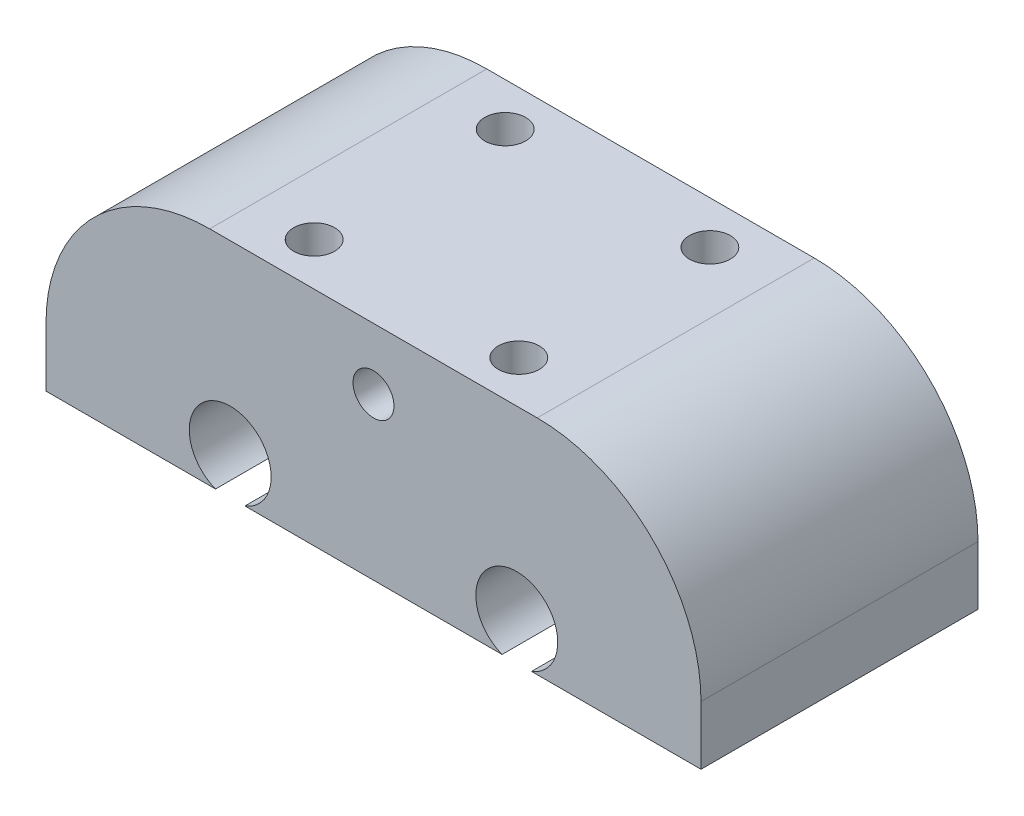
SolidWorks part; units mm, degrees
ref_plane "Front Plane" through (0, 0, 0) normal (0, 0, 1) x (1, 0, 0)
ref_plane "Top Plane" through (0, 0, 0) normal (0, 1, 0) x (1, 0, 0)
ref_plane "Right Plane" through (0, 0, 0) normal (1, 0, 0) x (0, 0, -1)
sketch "Sketch1" plane through (0, 0, 0) normal (0, 1, 0) x (1, 0, 0)
  line L1 (0, 0) -> (48, 0)
  line L2 (0, 0) -> (0, -20.3)
  line L3 (0, -20.3) -> (48, -20.3)
  line L4 (48, 0) -> (48, -20.3)
  dimension "D1" = 20.3
  dimension "D2" = 48
extrude "Boss-Extrude1" add sketch "Sketch1" along normal blind 16.3
sketch "Sketch2" plane through (0, 0, 20.3) normal (0, 0, 1) x (1, 0, 0)
  line L0 (0, 0) -> (48, 0) construction
  line L1 (0, 16.3) -> (0, 0) construction
  line L2 (48, 16.3) -> (48, 0) construction
  circle A0 centre (13.5, 2.8) radius 3
  circle A1 centre (34.5, 2.8) radius 3
  dimension "D1" = 6
  dimension "D2" = 6
  dimension "D3" = 2.8
  dimension "D4" = 2.8
  dimension "D5" = 13.5
  dimension "D6" = 13.5
extrude "Cut-Extrude1" cut sketch "Sketch2" against normal through all
ref_plane "Plane1" through (0, 0, 10.3) normal (0, 0, 1) x (1, 0, 0)
sketch "Sketch3" plane through (0, 0, 10.3) normal (0, 0, 1) x (1, 0, 0)
  line L2 (3.5, 2.8) -> (3.5, -6.25)
  line L3 (3.5, -6.25) -> (23.4955, -6.25)
  line L4 (23.4955, 3.0999) -> (23.4955, -6.25)
  line L6 (24.5, 2.8) -> (24.5, -6.25)
  line L7 (24.5, -6.25) -> (44.4955, -6.25)
  line L8 (44.4955, 3.0999) -> (44.4955, -6.25)
  arc A0 (23.4955, 3.0999) -> (3.5, 2.8) centre (13.5, 2.8) ccw
  arc A1 (44.4955, 3.0999) -> (24.5, 2.8) centre (34.5, 2.8) ccw
  dimension "D1" = 20
  dimension "D2" = 20
extrude "Cut-Extrude2" cut sketch "Sketch3" against normal mid plane 7
fillet "Fillet1" radius 12 2 edges at (48, 16.3, 10.15) (0, 16.3, 10.15)
ref_plane "打印面" through (0, -10, 0) normal (0, 1, 0) x (1, 0, 0)
sketch "Sketch4" plane through (0, 0, 0) normal (0, 0, -1) x (-1, 0, 0)
  line L0 (-36, 16.3) -> (-12, 16.3) construction
  circle A0 centre (-24, 11.8) radius 1.5
  dimension "D1" = 3
  dimension "D2" = 4.5
extrude "Cut-Extrude3" cut sketch "Sketch4" against normal through all
sketch "Sketch5" plane through (0, 16.3, 0) normal (0, 1, 0) x (1, 0, 0)
  line L0 (12, -20.3) -> (36, -20.3) construction
  circle A0 centre (31.5, -17.15) radius 1.5
  circle A1 centre (16.5, -17.15) radius 1.5
  circle A2 centre (16.5, -3.15) radius 1.5
  circle A3 centre (31.5, -3.15) radius 1.5
  point P11 (24, -20.3)
  dimension "D1" = 3
  dimension "D3" = 3.15
  dimension "D4" = 7.5
  dimension "D5" = 2
  dimension "D2" = 2
extrude "Cut-Extrude4" cut sketch "Sketch5" against normal blind 8
equation "\"滑动-垂直孔\"= 0.6"
equation "\"滑动-水平孔\"= 0.3"
equation "\"松动-垂直孔\"= 0.3"
equation "\"松动-水平孔\"= 0.1"
equation "\"正常-垂直孔\"= 0.15"
equation "\"正常-水平孔\"= 0"
equation "\"紧缩-垂直孔\"= 0"
equation "\"紧缩-水平孔\"= - 0.1"
equation "\"D2@Sketch2\"=\"正常-水平孔\"+6"
equation "\"D1@Sketch2\"=\"D2@Sketch2\""
equation "\"D1@Sketch1\"=\"松动-垂直孔\"+20"
equation "\"D4@Sketch2\"=\"D3@Sketch2\""
equation "\"D1@Sketch4\"=\"正常-水平孔\"+3"
equation "\"D1@Sketch5\"=\"紧缩-垂直孔\"+3"
equation "\"D3@Sketch5\"=\"D1@Sketch1\"/2-7"
